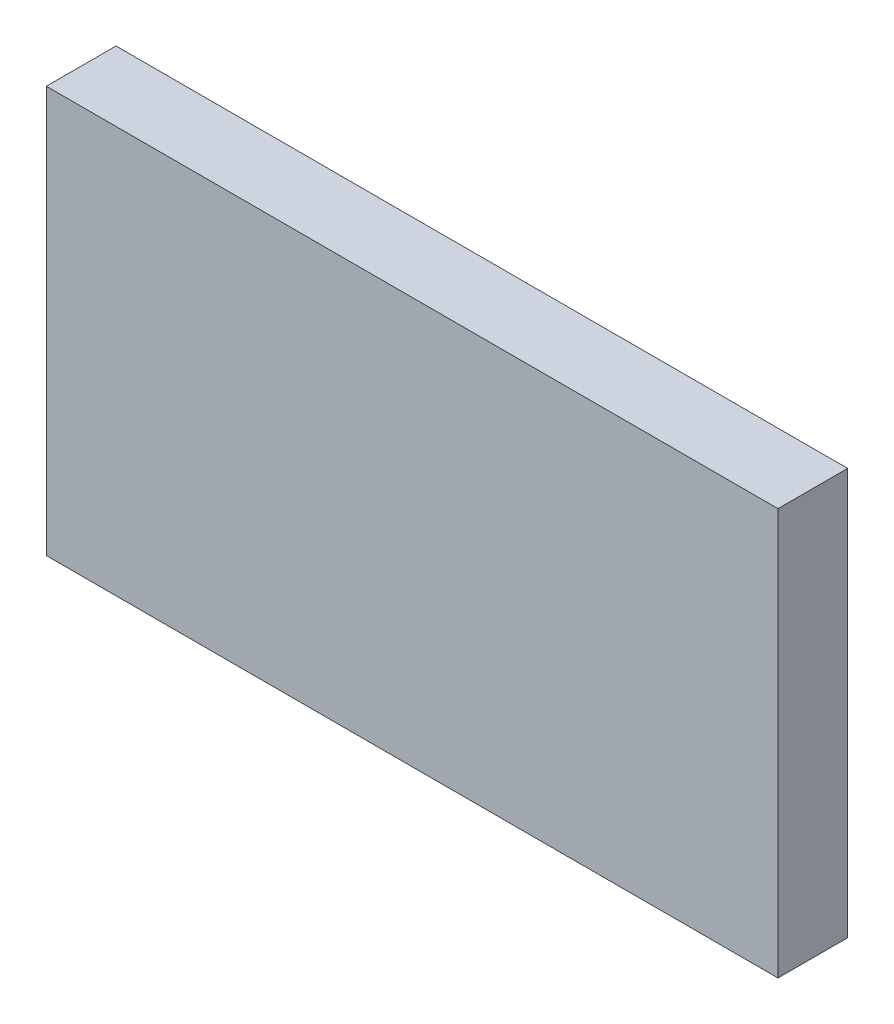
SolidWorks part; units mm, degrees
ref_plane "Front Plane" through (0, 0, 0) normal (0, 0, 1) x (1, 0, 0)
ref_plane "Top Plane" through (0, 0, 0) normal (0, 1, 0) x (1, 0, 0)
ref_plane "Right Plane" through (0, 0, 0) normal (1, 0, 0) x (0, 0, -1)
sketch "Sketch1" plane through (0, 0, 0) normal (0, 0, 1) x (1, 0, 0)
  line L1 (0, 0) -> (126, 0)
  line L2 (0, 0) -> (0, 70)
  line L3 (0, 70) -> (126, 70)
  line L4 (126, 0) -> (126, 70)
  dimension "D1" = 126
  dimension "D2" = 70
extrude "Boss-Extrude1" add sketch "Sketch1" along normal blind 12
